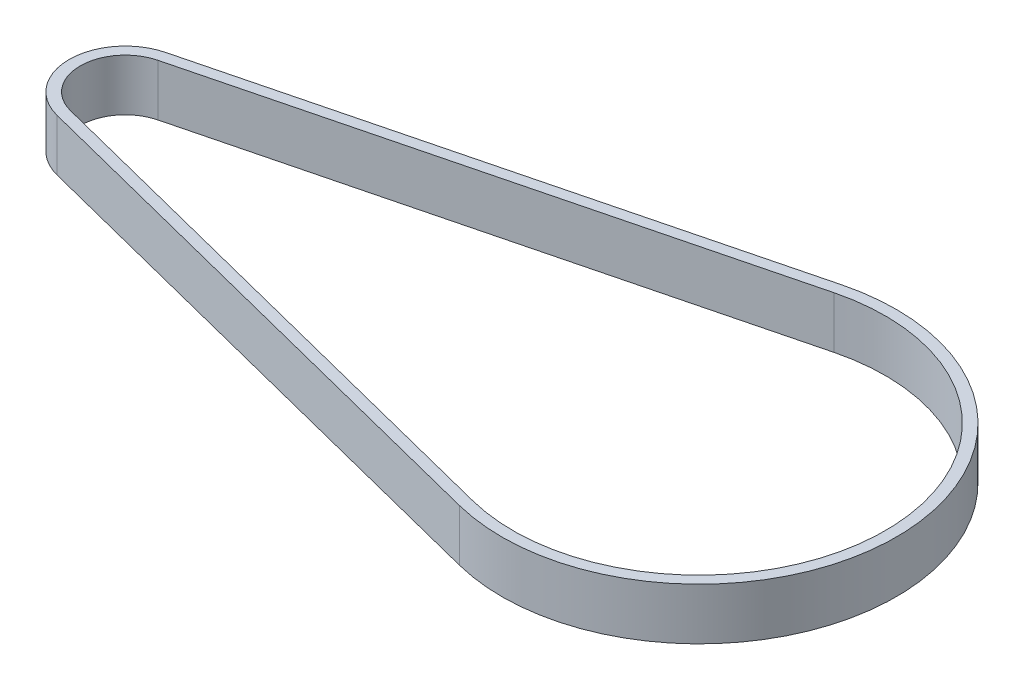
SolidWorks part; units mm, degrees
ref_plane "Front Plane" through (0, 0, 0) normal (0, 0, 1) x (1, 0, 0)
ref_plane "Top Plane" through (0, 0, 0) normal (0, 1, 0) x (1, 0, 0)
ref_plane "Right Plane" through (0, 0, 0) normal (1, 0, 0) x (0, 0, -1)
sketch "Sketch1" plane through (0, 0, 0) normal (0, 1, 0) x (1, 0, 0)
  line L0 (0, 0) -> (77.7, 0) construction
  line L1 (-1.4995, 5.9128) -> (71.5054, 24.4268)
  line L2 (-1.4995, -5.9128) -> (71.5054, -24.4268)
  line L3 (-1.8682, 7.3668) -> (71.1367, 25.8807)
  line L4 (-1.8682, -7.3668) -> (71.1367, -25.8807)
  arc A0 (-1.4995, 5.9128) -> (-1.4995, -5.9128) centre (0, 0) ccw
  arc A1 (71.5054, -24.4268) -> (71.5054, 24.4268) centre (77.7, 0) ccw
  arc A2 (71.1367, -25.8807) -> (71.1367, 25.8807) centre (77.7, 0) ccw
  arc A3 (-1.8682, 7.3668) -> (-1.8682, -7.3668) centre (0, 0) ccw
  dimension "D1" = 12.2
  dimension "D2" = 50.4
  dimension "D3" = 1.5
  dimension "D4" = 77.7
extrude "Boss-Extrude1" add sketch "Sketch1" along normal blind 7
